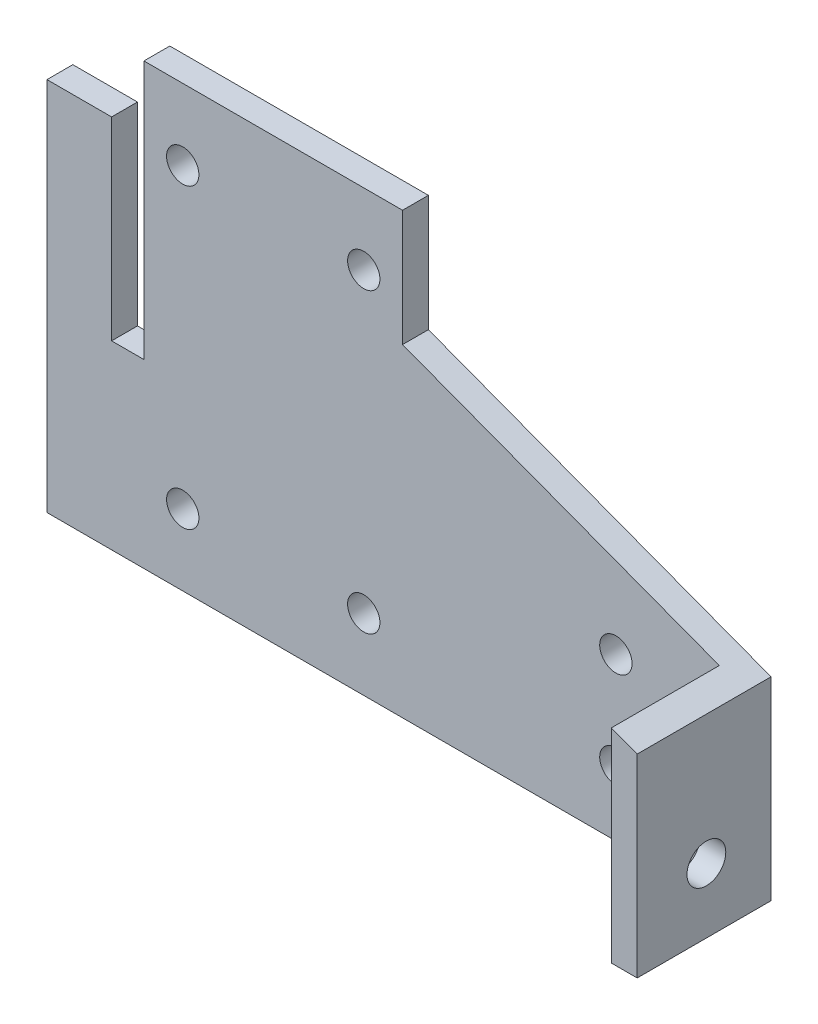
SolidWorks part; units mm, degrees
ref_plane "Спереди" through (0, 0, 0) normal (0, 0, 1) x (1, 0, 0)
ref_plane "Сверху" through (0, 0, 0) normal (0, 1, 0) x (1, 0, 0)
ref_plane "Справа" through (0, 0, 0) normal (1, 0, 0) x (0, 0, -1)
sketch "Эскиз1" plane through (0, 0, 0) normal (0, 0, 1) x (1, 0, 0)
  line L0 (35, 68) -> (35, 0) construction
  line L1 (0, 0) -> (108, 0)
  line L2 (0, 0) -> (0, 68)
  line L3 (0, 68) -> (55, 68)
  line L4 (108, 0) -> (108, 30)
  line L5 (21, 68) -> (21, 0) construction
  line L6 (55, 68) -> (55, 50)
  line L8 (49, 68) -> (49, 0) construction
  line L10 (108, 30) -> (55, 50)
  circle A0 centre (21, 57) radius 2.5
  circle A1 centre (49, 57) radius 2.5
  circle A2 centre (21, 11) radius 2.5
  circle A3 centre (49, 11) radius 2.5
  circle A4 centre (88, 10) radius 2.5
  circle A5 centre (88, 25) radius 2.5
  dimension "D8" = 5
  dimension "D9" = 5
  dimension "D10" = 5
  dimension "D11" = 5
  dimension "D18" = 5
  dimension "D20" = 5
  dimension "D1" = 108
  dimension "D2" = 68
  dimension "D3" = 55
  dimension "D4" = 30
  dimension "D5" = 35
  dimension "D6" = 14
  dimension "D7" = 14
  dimension "D12" = 46
  dimension "D13" = 46
  dimension "D14" = 11
  dimension "D15" = 11
  dimension "D16" = 20
  dimension "D17" = 10
  dimension "D19" = 20
  dimension "D21" = 15
extrude "Бобышка-Вытянуть1" add sketch "Эскиз1" along normal blind 4
sketch "Эскиз2" plane through (0, 0, 4) normal (0, 0, 1) x (1, 0, 0)
  line L1 (108, 0) -> (104, 0)
  line L2 (0, 0) -> (108, 0) construction
  line L3 (104, 0) -> (104, 31.5094)
  line L4 (108, 30) -> (55, 50) construction
  line L5 (104, 31.5094) -> (108, 30)
  line L6 (108, 30) -> (108, 0)
  dimension "D1" = 4
extrude "Бобышка-Вытянуть2" add sketch "Эскиз2" along normal blind 16.7
sketch "Эскиз3" plane through (108, 0, 0) normal (1, 0, 0) x (0, 0, -1)
  line L4 (0, 0) -> (0, 30) construction
  line L5 (-20.7, 0) -> (0, 0) construction
  circle A1 centre (-10, 10) radius 3
  dimension "D2" = 10
  dimension "D3" = 6
  dimension "D1" = 10
extrude "Вырез-Вытянуть1" cut sketch "Эскиз3" against normal blind 10
sketch "Эскиз4" plane through (0, 0, 4) normal (0, 0, 1) x (1, 0, 0)
  line L1 (0, 68) -> (15, 68)
  line L2 (0, 68) -> (0, 58)
  line L3 (0, 58) -> (10, 58)
  line L4 (15, 68) -> (15, 58)
  line L6 (15, 58) -> (15, 28)
  line L7 (15, 28) -> (10, 28)
  line L8 (10, 58) -> (10, 28)
  dimension "D1" = 15
  dimension "D2" = 10
  dimension "D3" = 40
  dimension "D4" = 5
extrude "Вырез-Вытянуть2" cut sketch "Эскиз4" against normal blind 10
